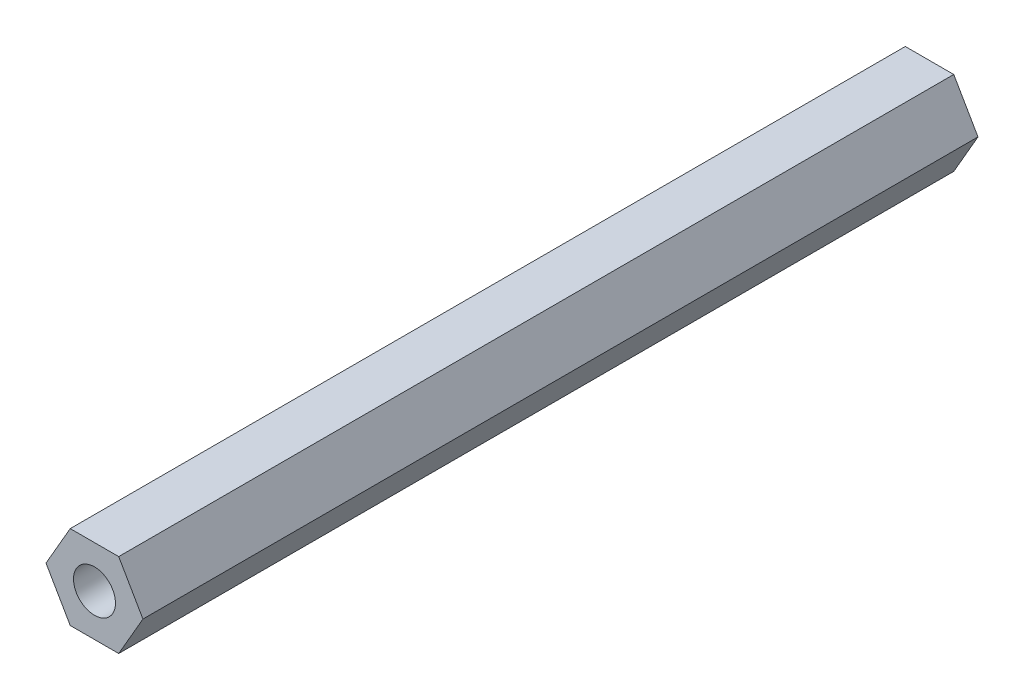
SolidWorks part; units mm, degrees
material "1060 Alloy"
ref_plane "Front Plane" through (0, 0, 0) normal (0, 0, 1) x (1, 0, 0)
ref_plane "Top Plane" through (0, 0, 0) normal (0, 1, 0) x (1, 0, 0)
ref_plane "Right Plane" through (0, 0, 0) normal (1, 0, 0) x (0, 0, -1)
sketch "Sketch1" plane through (0, 0, 0) normal (0, 0, 1) x (1, 0, 0)
  line L1 (3.6662, 6.35) -> (-3.6662, 6.35)
  line L2 (-3.6662, 6.35) -> (-7.3323, 0)
  line L3 (-7.3323, 0) -> (-3.6662, -6.35)
  line L4 (-3.6662, -6.35) -> (3.6662, -6.35)
  line L5 (3.6662, -6.35) -> (7.3323, 0)
  line L6 (7.3323, 0) -> (3.6662, 6.35)
  circle A0 centre (0, 0) radius 6.35 construction
  circle A1 centre (0, 0) radius 3.175
  dimension "D2" = 6.35
  dimension "D1" = 12.7
extrude "Boss-Extrude1" add sketch "Sketch1" along normal blind 126.3269
